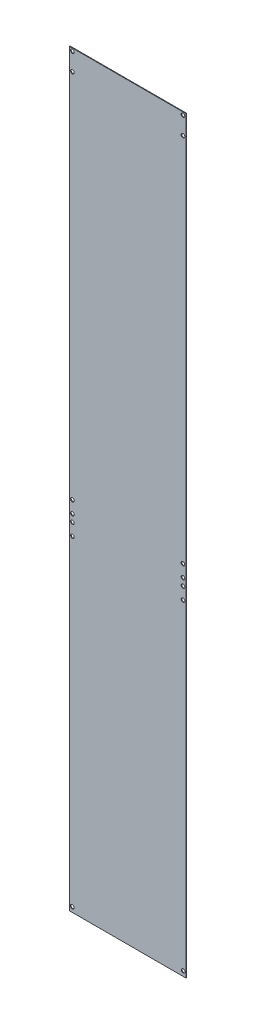
SolidWorks part; units mm, degrees
ref_plane "Front Plane" through (0, 0, 0) normal (0, 0, 1) x (1, 0, 0)
ref_plane "Top Plane" through (0, 0, 0) normal (0, 1, 0) x (1, 0, 0)
ref_plane "Right Plane" through (0, 0, 0) normal (1, 0, 0) x (0, 0, -1)
sketch "Sketch1" plane through (0, 0, 0) normal (0, 0, 1) x (1, 0, 0)
  line L1 (0, 0) -> (609.6, 0)
  line L2 (0, 0) -> (0, 3924.3)
  line L3 (0, 3924.3) -> (609.6, 3924.3)
  line L4 (609.6, 0) -> (609.6, 3924.3)
  dimension "D1" = 609.6
  dimension "D2" = 3924.3
extrude "Boss-Extrude1" add sketch "Sketch1" along normal blind 3.175
sketch "Sketch2" plane through (0, 0, 0) normal (0, 0, -1) x (-1, 0, 0)
  circle A0 centre (-13.9751, 25.4) radius 3.3782 construction
  circle A1 centre (-595.6249, 25.4) radius 3.3782 construction
  circle A2 centre (-15.0838, 1809.75) radius 3.3782 construction
  circle A3 centre (-15.0838, 1873.2449) radius 3.3782 construction
  circle A4 centre (-15.0838, 1771.65) radius 3.3782 construction
  circle A5 centre (-15.0838, 1708.1602) radius 3.3782 construction
  circle A6 centre (-594.5162, 1708.1602) radius 3.3782 construction
  circle A7 centre (-594.5162, 1771.65) radius 3.3782 construction
  circle A8 centre (-594.5162, 1809.75) radius 7.1437 construction
  circle A9 centre (-594.5162, 1873.2449) radius 3.3782 construction
  circle A10 centre (-594.5162, 1809.75) radius 3.3782 construction
  circle A11 centre (-594.5162, 1873.2449) radius 3.3782 construction
  circle A12 centre (-15.0838, 3816.35) radius 3.3782 construction
  circle A13 centre (-15.0838, 3909.2505) radius 3.3782 construction
  circle A14 centre (-594.5162, 3816.35) radius 3.3782 construction
  circle A15 centre (-594.5162, 3909.2505) radius 3.3782 construction
  circle A16 centre (-13.9751, 25.4) radius 3.3782
  circle A17 centre (-595.6249, 25.4) radius 3.3782
  circle A18 centre (-15.0838, 1809.75) radius 3.3782
  circle A19 centre (-15.0838, 1873.2449) radius 3.3782
  circle A20 centre (-15.0838, 1771.65) radius 3.3782
  circle A21 centre (-15.0838, 1708.1602) radius 3.3782
  circle A22 centre (-594.5162, 1708.1602) radius 3.3782
  circle A23 centre (-594.5162, 1771.65) radius 3.3782
  circle A24 centre (-594.5162, 1809.75) radius 7.1437
  circle A25 centre (-594.5162, 1873.2449) radius 3.3782
  circle A26 centre (-594.5162, 1809.75) radius 3.3782
  circle A27 centre (-594.5162, 1873.2449) radius 3.3782
  circle A28 centre (-15.0838, 3816.35) radius 3.3782
  circle A29 centre (-15.0838, 3909.2505) radius 3.3782
  circle A30 centre (-594.5162, 3816.35) radius 3.3782
  circle A31 centre (-594.5162, 3909.2505) radius 3.3782
sketch "Sketch3" plane through (0, 0, 0) normal (0, 0, -1) x (-1, 0, 0)
  circle A0 centre (-594.5162, 3909.2505) radius 9.525
  circle A1 centre (-594.5162, 3816.35) radius 9.525
  circle A2 centre (-594.5162, 1873.2449) radius 9.525
  circle A3 centre (-594.5162, 1809.75) radius 9.525
  circle A4 centre (-594.5162, 1771.65) radius 9.525
  circle A5 centre (-594.5162, 1708.1602) radius 9.525
  circle A6 centre (-595.6249, 25.4) radius 9.525
  circle A7 centre (-15.0838, 3909.2505) radius 9.525
  circle A8 centre (-15.0838, 3816.35) radius 9.525
  circle A9 centre (-15.0838, 1873.2449) radius 9.525
  circle A10 centre (-15.0838, 1809.75) radius 9.525
  circle A11 centre (-15.0838, 1771.65) radius 9.525
  circle A12 centre (-15.0838, 1708.1602) radius 9.525
  circle A13 centre (-13.9751, 25.4) radius 9.525
  dimension "D1" = 19.05
extrude "Cut-Extrude2" cut sketch "Sketch3" against normal through all
